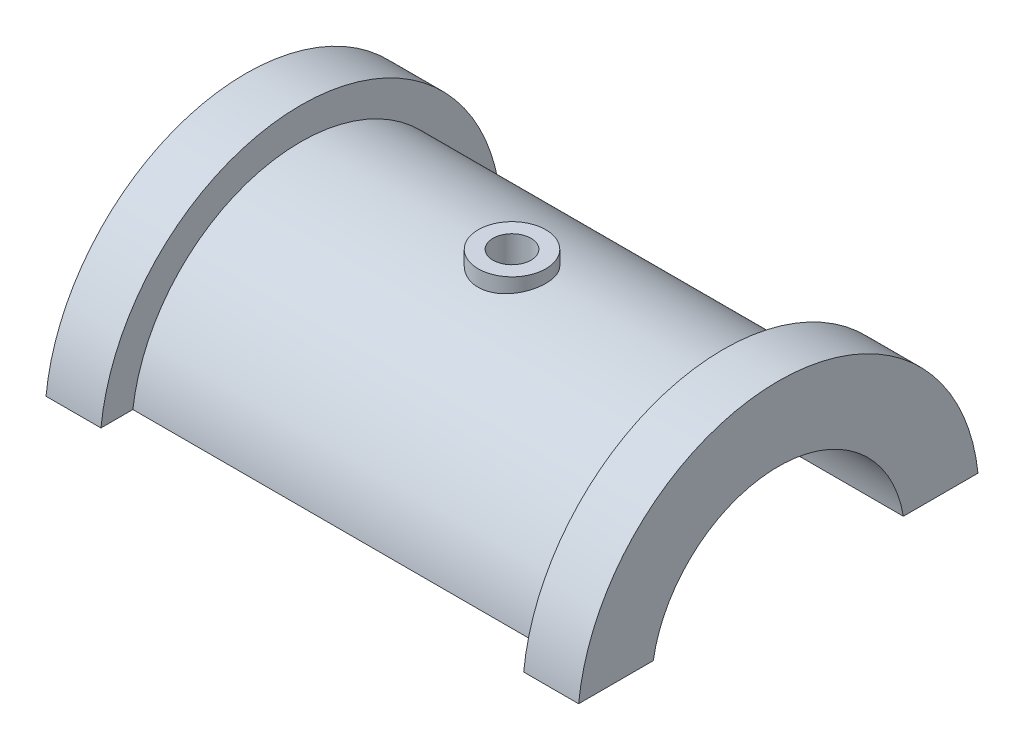
SolidWorks part; units mm, degrees
ref_plane "Front Plane" through (0, 0, 0) normal (0, 0, 1) x (1, 0, 0)
ref_plane "Top Plane" through (0, 0, 0) normal (0, 1, 0) x (1, 0, 0)
ref_plane "Right Plane" through (0, 0, 0) normal (1, 0, 0) x (0, 0, -1)
sketch "Sketch1" plane through (0, 0, 0) normal (0, 0, 1) x (1, 0, 0)
  line L0 (0, 0) -> (0, 47.5)
  line L1 (0, 47.5) -> (13, 47.5)
  line L2 (13, 47.5) -> (13, 40)
  line L3 (13, 40) -> (113, 40)
  line L4 (113, 40) -> (113, 47.5)
  line L5 (113, 47.5) -> (126, 47.5)
  line L6 (126, 47.5) -> (126, 0)
  line L7 (126, 0) -> (0, 0) construction
  line L8 (0, 0) -> (126, 0)
  dimension "D1" = 126
  dimension "D2" = 100
  dimension "D3" = 80
  dimension "D4" = 95
revolve "Revolve1" add sketch "Sketch1" angle 360 about L7
sketch "Sketch2" plane through (126, 0, 0) normal (1, 0, 0) x (0, 0, -1)
  circle A0 centre (0, 0) radius 30
  dimension "D1" = 60
extrude "Cut-Extrude1" cut sketch "Sketch2" against normal through all
ref_plane "Plane1" through (0, 43, 0) normal (0, 1, 0) x (1, 0, 0)
sketch "Sketch3" plane through (0, 43, 0) normal (0, 1, 0) x (1, 0, 0)
  line L0 (0, 47.5) -> (0, -47.5) construction
  circle A0 centre (63, 0) radius 8
  point P4 (0, 0)
  dimension "D1" = 16
  dimension "D2" = 63
extrude "Boss-Extrude1" add sketch "Sketch3" against normal up to next
hole_wizard "M10x1.0 Tapped Hole1" positions "Sketch4" profile "Sketch5" tap size "M10x1.0" standard "ANSI Metric"
sketch "Sketch4" plane through (0, 43, 0) normal (0, 1, 0) x (1, 0, 0)
  point P0 (63, 0)
sketch "Sketch5" plane through (63, 43, 0) normal (1, 0, 0) x (0, 0, 1)
  line L0 (0, 0) -> (0, 13)
  line L1 (0, 13) -> (4.5, 13)
  line L2 (4.5, 13) -> (4.5, 0)
  line L5 (4.5, 0) -> (0, 0)
  line L11 (0, -6.35) -> (0, 107.95) construction
  dimension "Thru Tap Drill Dia." = 9
  dimension "Thru Tap Drill Depth" = 13
sketch "Sketch6" plane through (126, 0, 0) normal (1, 0, 0) x (0, 0, -1)
  line L0 (-62.0855, 5) -> (59.6926, 5)
  dimension "D1" = 5
extrude "Cut-Extrude2" cut sketch "Sketch6" along normal through all and the other way through all flip side to cut contours L0
